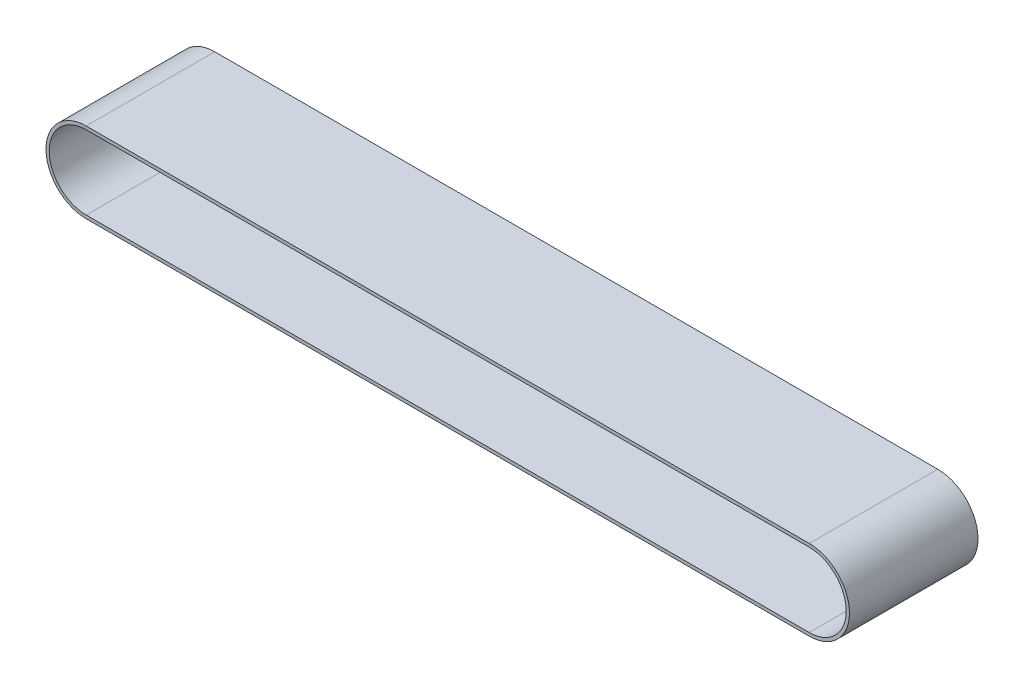
SolidWorks part; units mm, degrees
ref_plane "Ebene vorne" through (0, 0, 0) normal (0, 0, 1) x (1, 0, 0)
ref_plane "Ebene oben" through (0, 0, 0) normal (0, 1, 0) x (1, 0, 0)
ref_plane "Ebene rechts" through (0, 0, 0) normal (1, 0, 0) x (0, 0, -1)
sketch "Skizze1" plane through (0, 0, 0) normal (0, 0, 1) x (1, 0, 0)
  line L0 (0, 23) -> (435, 23) construction
  line L1 (0, 23) -> (435, 23)
  line L2 (435, 23) -> (450, 23)
  line L3 (450, -23) -> (0, -23)
  line L4 (0, 25) -> (435, 25)
  line L5 (435, 25) -> (450, 25)
  line L6 (450, -25) -> (0, -25)
  circle A0 centre (0, 0) radius 23 construction
  arc A1 (0, 23) -> (0, -23) centre (0, 0) ccw
  arc A2 (450, -23) -> (450, 23) centre (450, 0) ccw
  arc A3 (450, -25) -> (450, 25) centre (450, 0) ccw
  arc A4 (0, 25) -> (0, -25) centre (0, 0) ccw
  dimension "D1" = 2
extrude "Aufsatz-Linear austragen1" add sketch "Skizze1" against normal up to vertex (89.5 mm away) from vertex at -9.5
